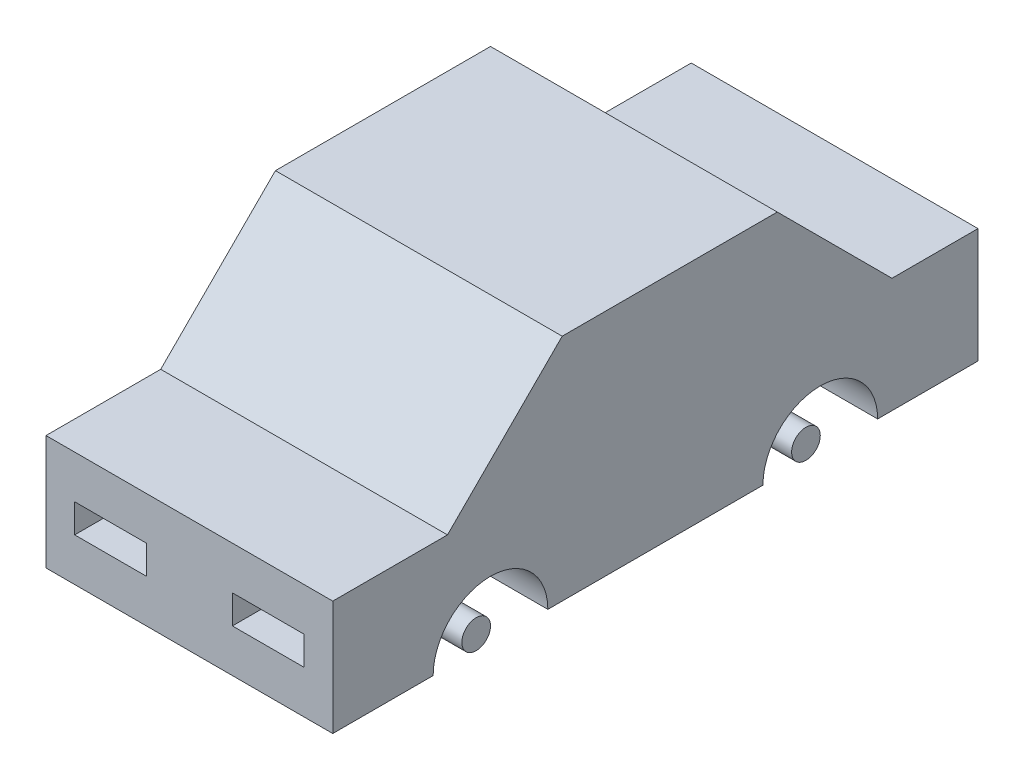
SolidWorks part; units mm, degrees
ref_plane "Front Plane" through (0, 0, 0) normal (0, 0, 1) x (1, 0, 0)
ref_plane "Top Plane" through (0, 0, 0) normal (0, 1, 0) x (1, 0, 0)
ref_plane "Right Plane" through (0, 0, 0) normal (1, 0, 0) x (0, 0, -1)
sketch "Car_Profile" plane through (0, 0, 0) normal (1, 0, 0) x (0, 0, -1)
  line L1 (2250, 0) -> (2250, 800)
  line L2 (2250, 800) -> (1650, 800)
  line L3 (1650, 800) -> (850, 1600)
  line L4 (850, 1600) -> (-650, 1600)
  line L5 (-650, 1600) -> (-1450, 800)
  line L6 (-1450, 800) -> (-2250, 800)
  line L7 (-2250, 800) -> (-2250, 0)
  line L11 (-2250, 0) -> (2250, 0)
  dimension "D1" = 4500
  dimension "D4" = 600
  dimension "D5" = 135
  dimension "D6" = 800
  dimension "D7" = 800
  dimension "D8" = 800
  dimension "D9" = 1500
extrude "Boss-Extrude1" add sketch "Car_Profile" along normal mid plane 2000
sketch "Sketch4" plane through (1000, 0, 0) normal (1, 0, 0) x (0, 0, -1)
  line L0 (-2250, 0) -> (2250, 0) construction
  line L1 (-750, 0) -> (-1550, 0)
  line L2 (750, 0) -> (1550, 0)
  arc A0 (-1550, 0) -> (-750, 0) centre (-1150, 0) cw
  arc A1 (1550, 0) -> (750, 0) centre (1150, 0) ccw
  dimension "D1" = 400
  dimension "D2" = 400
  dimension "D3" = 750
  dimension "D4" = 750
extrude "Cut-Extrude3" cut sketch "Sketch4" against normal blind 400
sketch "Sketch6" plane through (-1000, 0, 0) normal (-1, 0, 0) x (0, 0, 1)
  line L0 (2250, 0) -> (-2250, 0) construction
  line L1 (-750, 0) -> (-1550, 0)
  line L2 (750, 0) -> (1550, 0)
  arc A0 (-750, 0) -> (-1550, 0) centre (-1150, 0) ccw
  arc A1 (1550, 0) -> (750, 0) centre (1150, 0) ccw
  dimension "D1" = 400
  dimension "D2" = 400
  dimension "D3" = 750
  dimension "D4" = 750
extrude "Cut-Extrude4" cut sketch "Sketch6" against normal blind 400
sketch "Sketch7" plane through (0, 0, 0) normal (1, 0, 0) x (0, 0, -1)
  line L0 (-1550, 0) -> (-750, 0) construction
  line L1 (750, 0) -> (1550, 0) construction
  circle A0 centre (-1150, 0) radius 100
  circle A1 centre (1150, 0) radius 100
  dimension "D1" = 200
  dimension "D2" = 200
extrude "Boss-Extrude2" add sketch "Sketch7" along normal mid plane 1800
sketch "Sketch8" plane through (0, 0, 2250) normal (0, 0, 1) x (1, 0, 0)
  line L0 (0, 0) -> (0, 800) construction
  line L1 (1000, 800) -> (-1000, 800) construction
  line L2 (-1000, 800) -> (-1000, 0) construction
  line L3 (-800, 500) -> (-300, 500)
  line L4 (-800, 500) -> (-800, 300)
  line L5 (-800, 300) -> (-300, 300)
  line L6 (-300, 500) -> (-300, 300)
  line L8 (800, 300) -> (300, 300)
  line L9 (300, 500) -> (300, 300)
  line L10 (800, 500) -> (300, 500)
  line L11 (800, 500) -> (800, 300)
  dimension "D1" = 500
  dimension "D2" = 200
  dimension "D3" = 200
  dimension "D4" = 300
extrude "Cut-Extrude5" cut sketch "Sketch8" against normal blind 300
